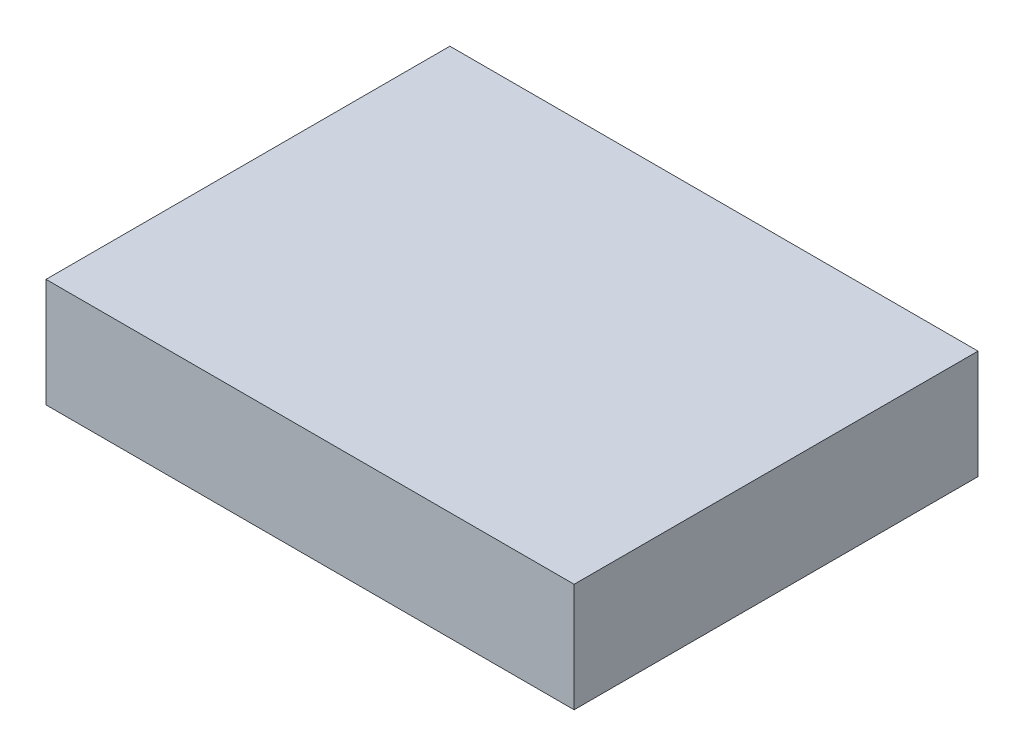
SolidWorks part; units mm, degrees
ref_plane "Front Plane" through (0, 0, 0) normal (0, 0, 1) x (1, 0, 0)
ref_plane "Top Plane" through (0, 0, 0) normal (0, 1, 0) x (1, 0, 0)
ref_plane "Right Plane" through (0, 0, 0) normal (1, 0, 0) x (0, 0, -1)
sketch "Sketch1" plane through (0, 0, 0) normal (0, 1, 0) x (1, 0, 0)
  line L1 (-21.59, -16.51) -> (21.59, -16.51)
  line L2 (-21.59, -16.51) -> (-21.59, 16.51)
  line L3 (-21.59, 16.51) -> (21.59, 16.51)
  line L4 (21.59, -16.51) -> (21.59, 16.51)
  line L5 (-21.59, -16.51) -> (21.59, 16.51) construction
  line L6 (-21.59, 16.51) -> (21.59, -16.51) construction
  point P0 (0, 0)
  dimension "D1" = 43.18
  dimension "D2" = 33.02
extrude "Boss-Extrude1" add sketch "Sketch1" along normal blind 8.89
